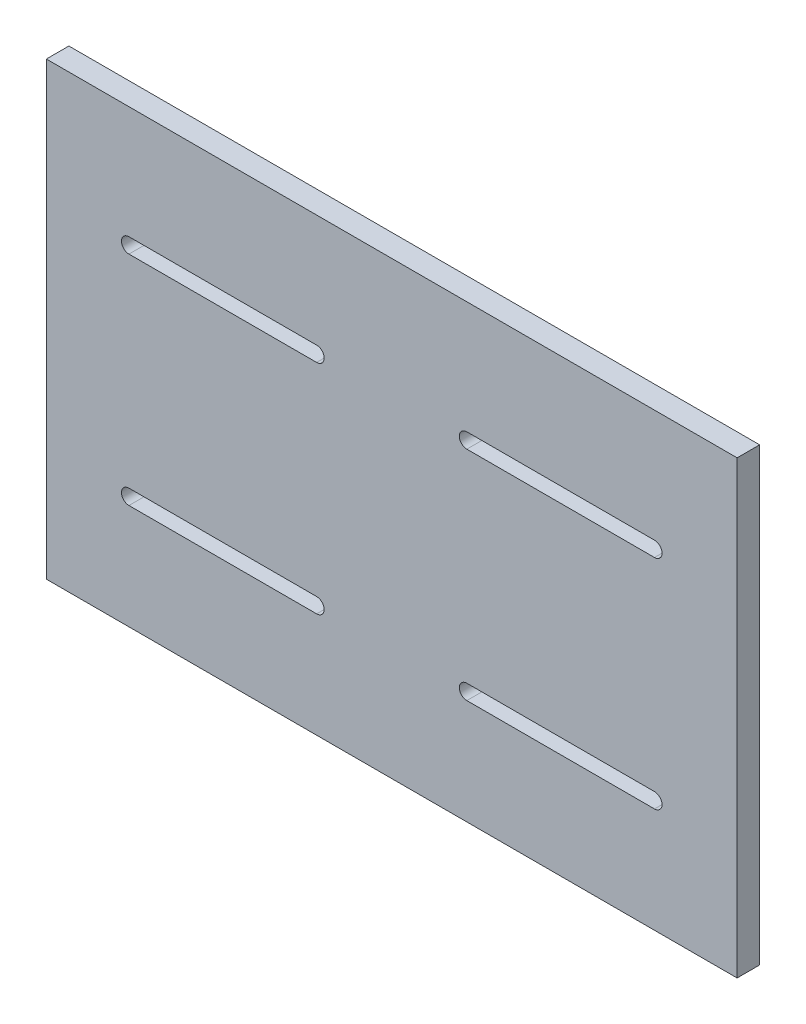
SolidWorks part; units mm, degrees
ref_plane "Front Plane" through (0, 0, 0) normal (0, 0, 1) x (1, 0, 0)
ref_plane "Top Plane" through (0, 0, 0) normal (0, 1, 0) x (1, 0, 0)
ref_plane "Right Plane" through (0, 0, 0) normal (1, 0, 0) x (0, 0, -1)
sketch "Sketch1" plane through (0, 0, 0) normal (0, 0, 1) x (1, 0, 0)
  line L1 (-46, 30) -> (46, 30)
  line L2 (-46, 30) -> (-46, -30)
  line L3 (-46, -30) -> (46, -30)
  line L4 (46, 30) -> (46, -30)
  line L5 (-46, 30) -> (46, -30) construction
  line L6 (-46, -30) -> (46, 30) construction
  point P0 (0, 0)
  dimension "D1" = 92
  dimension "D2" = 60
extrude "Boss-Extrude1" add sketch "Sketch1" along normal blind 3
sketch "Sketch2" plane through (0, 0, 3) normal (0, 0, 1) x (1, 0, 0)
  line L0 (-66.9812, 0) -> (67.4228, 0) construction
  line L1 (-35, 21.8609) -> (-35, -22.4497) construction
  line L2 (35, 21.8609) -> (35, -22.4497) construction
  line L3 (-35, 14) -> (-10, 14) construction
  line L4 (-35, 15) -> (-10, 15)
  line L5 (-35, 13) -> (-10, 13)
  line L6 (-35, -15) -> (-10, -15) construction
  line L7 (-35, -14) -> (-10, -14)
  line L8 (-35, -16) -> (-10, -16)
  line L9 (35, 14) -> (10, 14) construction
  line L10 (35, 13) -> (10, 13)
  line L11 (35, 15) -> (10, 15)
  line L12 (35, -15) -> (10, -15) construction
  line L13 (35, -16) -> (10, -16)
  line L14 (35, -14) -> (10, -14)
  arc A0 (-35, 15) -> (-35, 13) centre (-35, 14) ccw
  arc A1 (-10, 13) -> (-10, 15) centre (-10, 14) ccw
  arc A2 (-35, -14) -> (-35, -16) centre (-35, -15) ccw
  arc A3 (-10, -16) -> (-10, -14) centre (-10, -15) ccw
  arc A4 (35, 13) -> (35, 15) centre (35, 14) ccw
  arc A5 (10, 15) -> (10, 13) centre (10, 14) ccw
  arc A6 (35, -16) -> (35, -14) centre (35, -15) ccw
  arc A7 (10, -14) -> (10, -16) centre (10, -15) ccw
  point P9 (-22.5, 14)
  point P16 (-22.5, -15)
  point P23 (22.5, 14)
  point P30 (22.5, -15)
  dimension "D1" = 35
  dimension "D2" = 35
  dimension "D3" = 25
  dimension "D4" = 25
  dimension "D5" = 25
  dimension "D6" = 25
  dimension "D7" = 14
  dimension "D8" = 14
  dimension "D9" = 14
  dimension "D10" = 14
  dimension "D11" = 2
  dimension "D12" = 2
  dimension "D13" = 2
  dimension "D14" = 2
extrude "Cut-Extrude1" cut sketch "Sketch2" against normal blind 3
